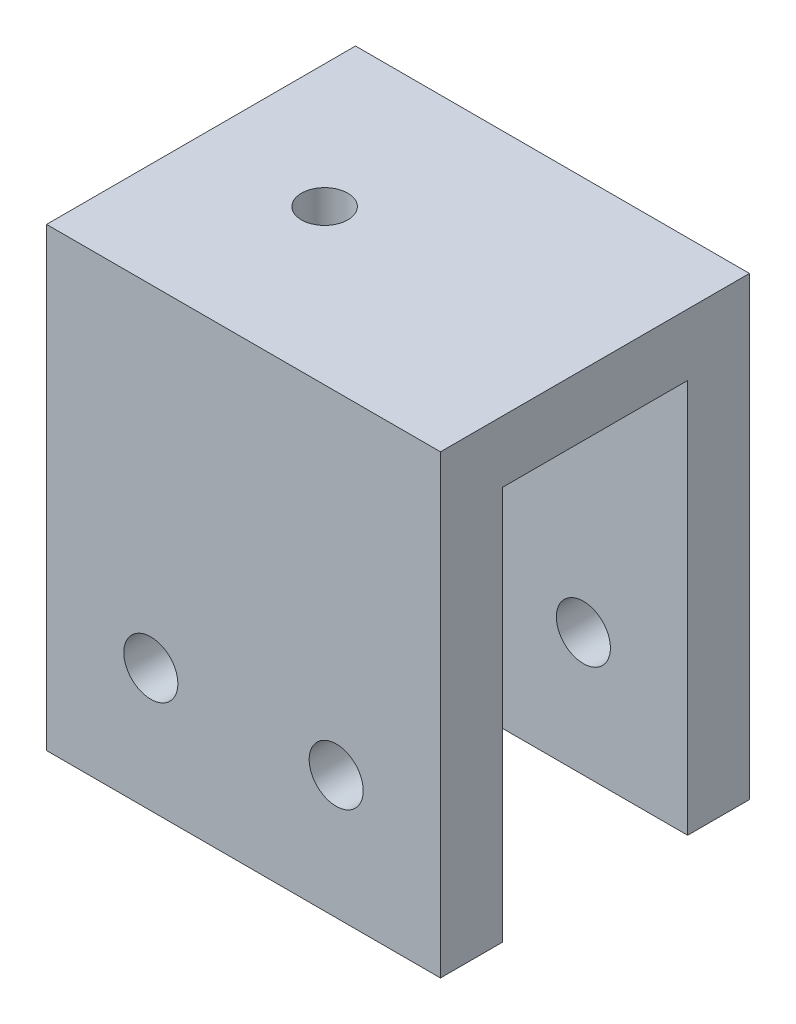
SolidWorks part; units mm, degrees
ref_plane "Płaszczyzna przednia" through (0, 0, 0) normal (0, 0, 1) x (1, 0, 0)
ref_plane "Płaszczyzna górna" through (0, 0, 0) normal (0, 1, 0) x (1, 0, 0)
ref_plane "Płaszczyzna prawa" through (0, 0, 0) normal (1, 0, 0) x (0, 0, -1)
sketch "Sketch1" plane through (0, 0, 0) normal (0, 0, 1) x (1, 0, 0)
  line L1 (0, 0) -> (-12.75, 0)
  line L2 (0, 0) -> (0, 12.75)
  line L3 (0, 12.75) -> (-12.75, 12.75)
  line L4 (-12.75, 0) -> (-12.75, 12.75)
  line L5 (0, 0) -> (-12.75, 12.75) construction
  line L6 (0, 12.75) -> (-12.75, 0) construction
  point P4 (-6.375, 6.375)
  dimension "D1" = 12.75
  dimension "D2" = 12.75
extrude "Boss-Extrude1" add sketch "Sketch1" along normal blind 2 contours L2 L1 L4 L3
ref_plane "Plane1" through (0, 0, -6) normal (0, 0, -1) x (-1, 0, 0)
sketch "Sketch2" plane through (0, 0, -6) normal (0, 0, -1) x (-1, 0, 0)
  line L4 (12.75, 12.75) -> (0, 12.75)
  line L5 (0, 12.75) -> (0, 0)
  line L6 (0, 0) -> (12.75, 0)
  line L7 (12.75, 0) -> (12.75, 12.75)
  line L8 (12.75, 12.75) -> (0, 12.75)
  line L9 (0, 12.75) -> (0, 0)
  line L10 (0, 0) -> (12.75, 0)
  line L11 (12.75, 0) -> (12.75, 12.75)
  dimension "D1" = 0
extrude "Boss-Extrude2" add sketch "Sketch2" along normal blind 2 separate body
sketch "Sketch3" plane through (0, 12.75, 0) normal (0, 1, 0) x (1, 0, 0)
  line L1 (0, -2) -> (-12.75, -2)
  line L2 (0, -2) -> (0, 8)
  line L3 (0, 8) -> (-12.75, 8)
  line L4 (-12.75, -2) -> (-12.75, 8)
  line L5 (0, -2) -> (-12.75, 8) construction
  line L6 (0, 8) -> (-12.75, -2) construction
  point P4 (-6.375, 3)
extrude "Boss-Extrude3" add sketch "Sketch3" along normal blind 2
hole_wizard "Ø1.0mm Dowel Hole1" positions "Sketch4" profile "Sketch5" hole size "Ø1.0" standard "ANSI Metric" end condition through all
sketch "Sketch4" plane through (0, 0, 2) normal (0, 0, 1) x (1, 0, 0)
  line L0 (-12.75, 0) -> (-12.75, 14.75) construction
  line L1 (0, 0) -> (-12.75, 0) construction
  point P0 (-9.375, 4)
  point P2 (-3.375, 4)
  point P5 (0, 0)
  dimension "D1" = 6
  dimension "D2" = 3.375
  dimension "D3" = 4
sketch "Sketch5" plane through (-9.375, 4, 2) normal (1, 0, 0) x (0, -1, 0)
  line L0 (0, 0) -> (0, 10)
  line L1 (0, 10) -> (0.875, 10)
  line L2 (0.875, 10) -> (0.875, 0)
  line L5 (0.875, 0) -> (0, 0)
  line L11 (0, -6.35) -> (0, 107.95) construction
  dimension "Thru Hole Dia." = 1.75
  dimension "Thru Hole Depth" = 10
hole_wizard "Ø1.0mm Dowel Hole2" positions "Sketch6" profile "Sketch7" hole size "Ø1.0" standard "ANSI Metric" end condition through all
sketch "Sketch6" plane through (0, 14.75, 0) normal (0, 1, 0) x (1, 0, 0)
  line L0 (-12.75, 8) -> (-12.75, -2) construction
  line L4 (0, 8) -> (-12.75, 8) construction
  point P0 (-8.75, 3)
  point P9 (-8.2127, 8)
  point P18 (-11.2876, -2)
  dimension "D1" = 4
  dimension "D2" = 5
sketch "Sketch7" plane through (-8.75, 14.75, -3) normal (1, 0, 0) x (0, 0, 1)
  line L0 (0, 0) -> (0, 14.75)
  line L1 (0, 14.75) -> (0.75, 14.75)
  line L2 (0.75, 14.75) -> (0.75, 0)
  line L5 (0.75, 0) -> (0, 0)
  line L11 (0, -6.35) -> (0, 107.95) construction
  dimension "Thru Hole Dia." = 1.5
  dimension "Thru Hole Depth" = 14.75
